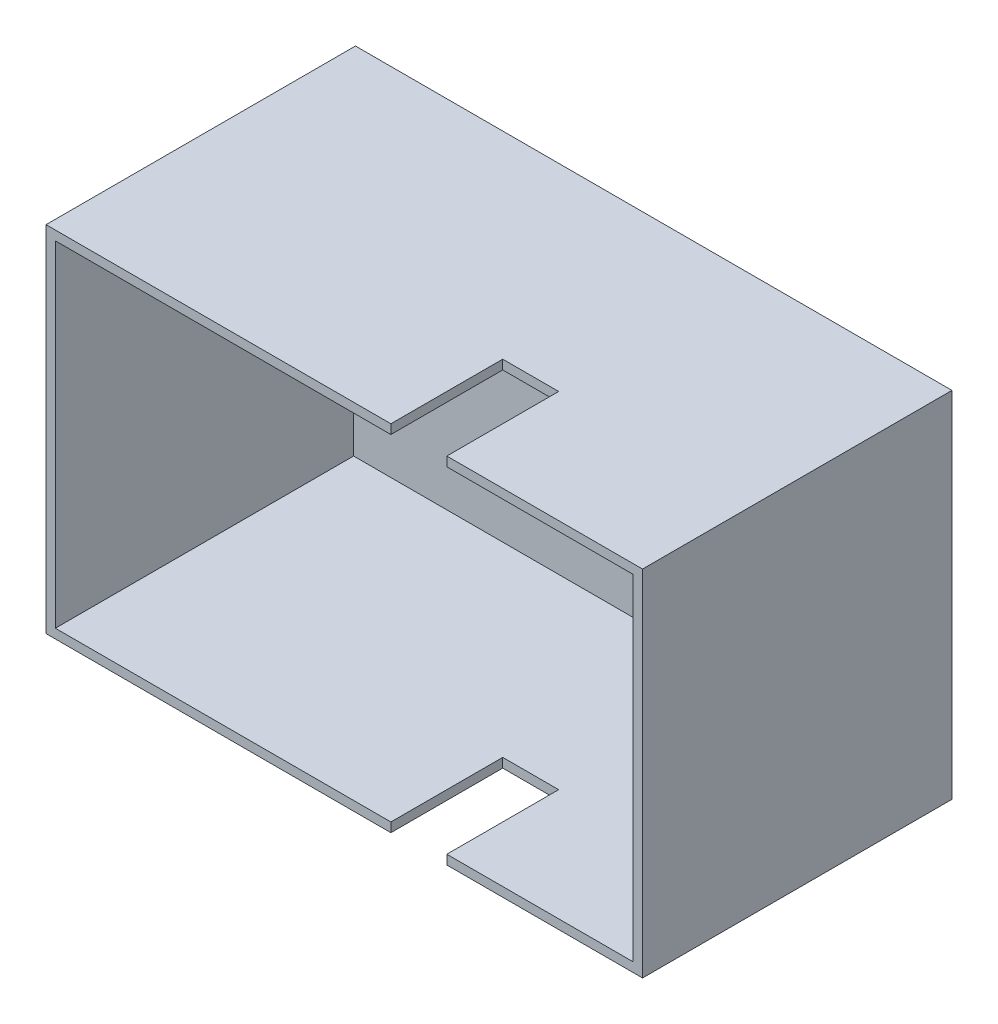
SolidWorks part; units mm, degrees
material "5052-H32"
ref_plane "Front Plane" through (0, 0, 0) normal (0, 0, 1) x (1, 0, 0)
ref_plane "Top Plane" through (0, 0, 0) normal (0, 1, 0) x (1, 0, 0)
ref_plane "Right Plane" through (0, 0, 0) normal (1, 0, 0) x (0, 0, -1)
sketch "ｽｹｯﾁ1" plane through (0, 0, 0) normal (0, 0, 1) x (1, 0, 0)
  line L0 (-80, 47.5) -> (80, 47.5)
  line L1 (-77.5, 45) -> (77.5, 45)
  line L2 (-77.5, 45) -> (-77.5, -45)
  line L3 (-77.5, -45) -> (77.5, -45)
  line L4 (77.5, 45) -> (77.5, -45)
  line L5 (-77.5, 45) -> (77.5, -45) construction
  line L6 (-77.5, -45) -> (77.5, 45) construction
  line L7 (80, 47.5) -> (80, -47.5)
  line L8 (-80, -47.5) -> (80, -47.5)
  line L9 (-80, 47.5) -> (-80, -47.5)
  point P0 (0, 0)
  dimension "D1" = 90
  dimension "D2" = 155
  dimension "D3" = 2.5
extrude "ﾎﾞｽ - 押し出し1" add sketch "ｽｹｯﾁ1" along normal blind 80
sketch "ｽｹｯﾁ3" plane through (0, 0, 0) normal (0, 0, -1) x (-1, 0, 0)
  line L0 (-80, 47.5) -> (80, 47.5) construction
  line L1 (-80, 47.5) -> (80, 47.5)
  line L2 (80, -47.5) -> (-80, -47.5) construction
  line L3 (80, 47.5) -> (80, -47.5) construction
  line L4 (-80, -47.5) -> (-80, 47.5) construction
  line L5 (80, -47.5) -> (-80, -47.5)
  line L6 (80, 47.5) -> (80, -47.5)
  line L7 (-80, -47.5) -> (-80, 47.5)
extrude "ﾎﾞｽ - 押し出し2" add sketch "ｽｹｯﾁ3" along normal blind 3
sketch "ｽｹｯﾁ4" plane through (0, 0, 0) normal (0, 0, 1) x (1, 0, 0)
  line L0 (-68.4068, 0) -> (71.4204, 0) construction
  circle A0 centre (0, 0) radius 4
  circle A1 centre (-56, 0) radius 4
  circle A2 centre (56, 0) radius 4
  dimension "D1" = 8
  dimension "D2" = 56
  dimension "D3" = 56
extrude "ｶｯﾄ - 押し出し1" cut sketch "ｽｹｯﾁ4" against normal blind 10
sketch "ｽｹｯﾁ5" plane through (0, -47.5, 0) normal (0, -1, 0) x (1, 0, 0)
  line L0 (-80, 80) -> (80, 80) construction
  line L1 (12.5, 80) -> (12.5, 50)
  line L2 (27.5, 50) -> (27.5, 80)
  line L3 (27.5, 80) -> (12.5, 80)
  line L4 (12.5, 50) -> (27.5, 50)
  line L6 (80, 80) -> (80, -3) construction
  dimension "D1" = 15
  dimension "D2" = 52.5
  dimension "D3" = 30
extrude "ｶｯﾄ - 押し出し2" cut sketch "ｽｹｯﾁ5" against normal through all
